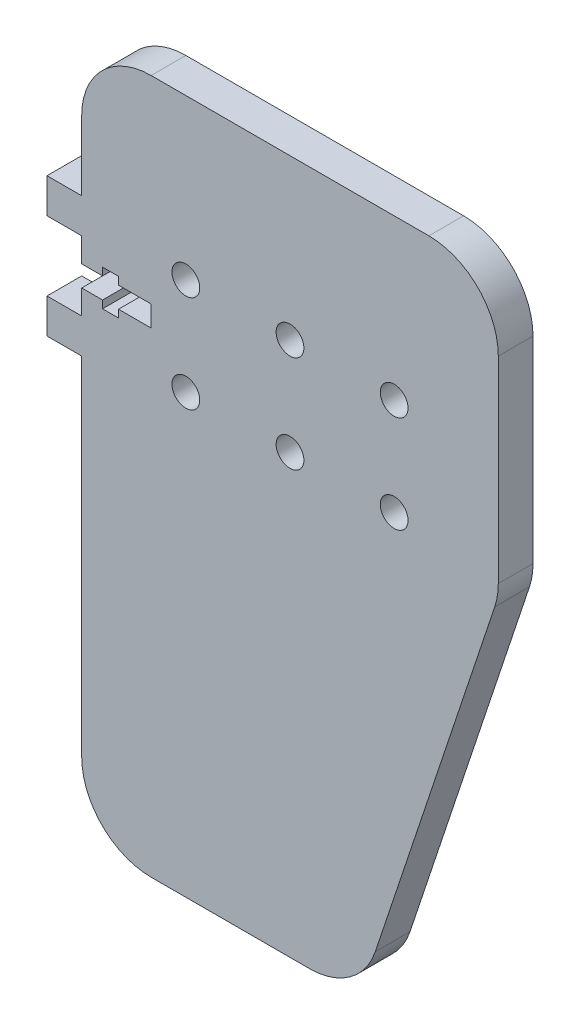
SolidWorks part; units mm, degrees
ref_plane "Plan de face" through (0, 0, 0) normal (0, 0, 1) x (1, 0, 0)
ref_plane "Plan de dessus" through (0, 0, 0) normal (0, 1, 0) x (1, 0, 0)
ref_plane "Plan de droite" through (0, 0, 0) normal (1, 0, 0) x (0, 0, -1)
sketch "Esquisse1" plane through (0, 0, 0) normal (0, 0, 1) x (1, 0, 0)
  line L0 (0, 391.1056) -> (0, -367.5965) construction
  line L1 (0, 0) -> (440.261, 0) construction
  line L2 (0, 80) -> (0, 100)
  line L3 (0, 100) -> (60, 100)
  line L4 (60, 100) -> (60, 60)
  line L5 (60, 60) -> (40, 0)
  line L6 (0, 0) -> (40, 0)
  line L8 (0, 0) -> (0, 60)
  line L9 (15, 77) -> (45, 77) construction
  circle A0 centre (15, 77) radius 2
  circle A1 centre (30, 77) radius 2
  circle A2 centre (45, 77) radius 2
  circle A3 centre (45, 63) radius 2
  circle A4 centre (30, 63) radius 2
  circle A5 centre (15, 63) radius 2
  point P11 (41.6371, 233.2536)
  point P12 (80, 317.2354)
  point P20 (0, 0)
  line B0 (3, 72.6) -> (5.3, 72.6)
  line B1 (5.3, 68.5) -> (10, 68.5)
  line B2 (10, 71.5) -> (5.3, 71.5)
  line B3 (5.3, 72.6) -> (5.3, 71.5)
  line B4 (0, 70) -> (11.2208, 70) construction
  line B5 (0, 71.5) -> (0, 75)
  line B6 (-5, 75) -> (-5, 80)
  line B7 (-5, 80) -> (0, 80)
  line B8 (-5, 75) -> (0, 75)
  line B9 (0, 68.5) -> (0, 65)
  line B10 (0, 65) -> (-5, 65)
  line B11 (-5, 65) -> (-5, 60)
  line B12 (-5, 60) -> (0, 60)
  line B13 (0, 71.5) -> (0, 68.5) construction
  line B14 (0, 68.5) -> (3, 68.5)
  line B15 (5.3, 68.5) -> (5.3, 67.4)
  line B16 (3, 67.4) -> (3, 68.5)
  line B17 (10, 68.5) -> (10, 71.5)
  line B18 (3, 71.5) -> (3, 72.6)
  line B19 (5.3, 67.4) -> (3, 67.4)
  line B20 (3, 71.5) -> (0, 71.5)
  line B21 (10, 70) -> (0, 70) construction
  dimension "D10" = 4
  dimension "D2" = 20
  dimension "D3" = 40
  dimension "D4" = 40
  dimension "D5" = 100
  dimension "D6" = 60
  dimension "D7" = 15
  dimension "D8" = 15
  dimension "D9" = 15
  dimension "D11" = 7
sketch_block_instance "Insert M3 plots ep 5mm-1"
sketch_block "Insert M3 plots ep 5mm" parameters "D1"=10, "D2"=5, "D3"=5
sketch_block_instance "Decoupe Insert M3-4"
sketch_block "Decoupe Insert M3" parameters "D1"=5.2, "D2"=3, "D3"=2.3, "D4"=3, "D5"=10
extrude "Boss.-Extru.1" add sketch "Esquisse1" along normal blind 5
fillet "Congé1" radius 10 5 edges at (0, 100, 2.5) (60, 100, 2.5) (60, 60, 2.5) (0, 0, 2.5) (40, 0, 2.5)
